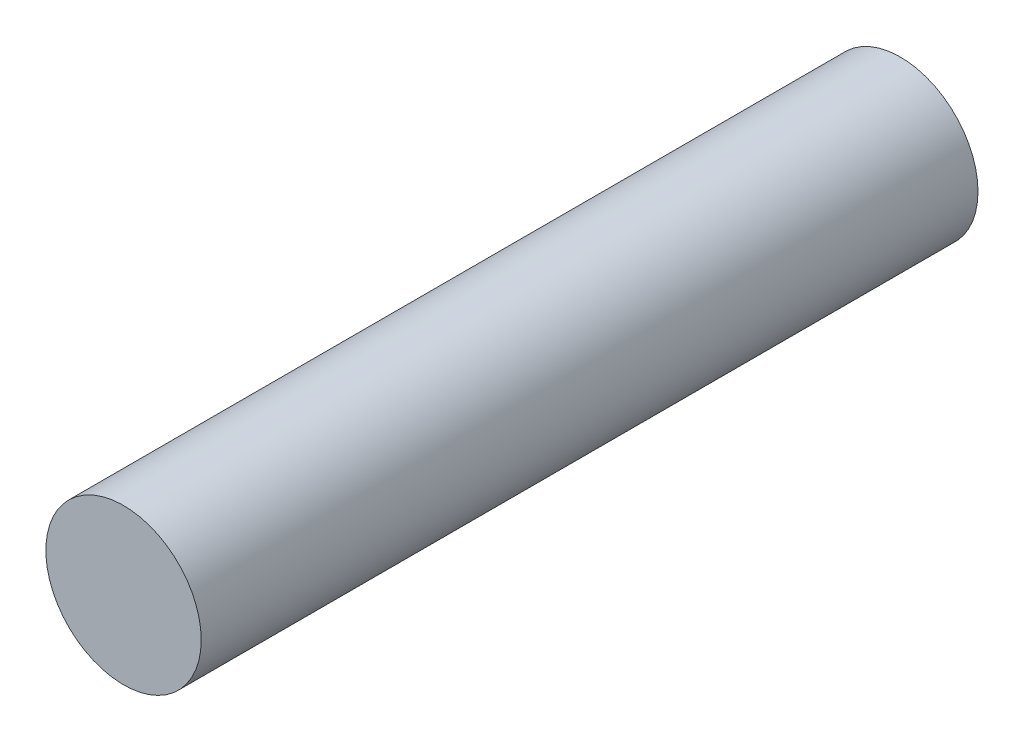
SolidWorks part; units mm, degrees
ref_plane "正面" through (0, 0, 0) normal (0, 0, 1) x (1, 0, 0)
ref_plane "平面" through (0, 0, 0) normal (0, 1, 0) x (1, 0, 0)
ref_plane "右側面" through (0, 0, 0) normal (1, 0, 0) x (0, 0, -1)
sketch "ｽｹｯﾁ1" plane through (0, 0, 0) normal (0, 0, 1) x (1, 0, 0)
  circle A0 centre (0, 0) radius 5
  point P3 (0, 0)
  dimension "D1" = 10
extrude "ﾎﾞｽ - 押し出し1" add sketch "ｽｹｯﾁ1" along normal blind 50
